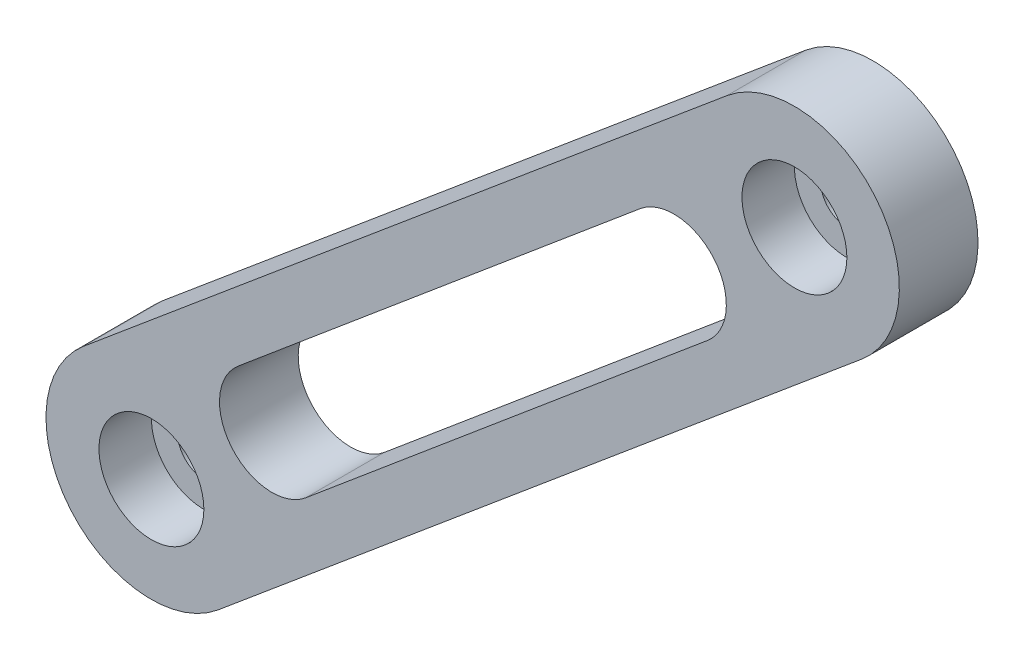
SolidWorks part; units mm, degrees
ref_plane "Front Plane" through (0, 0, 0) normal (0, 0, 1) x (1, 0, 0)
ref_plane "Top Plane" through (0, 0, 0) normal (0, 1, 0) x (1, 0, 0)
ref_plane "Right Plane" through (0, 0, 0) normal (1, 0, 0) x (0, 0, -1)
sketch "Sketch1" plane through (0, 0, 0) normal (0, 0, 1) x (1, 0, 0)
  line L0 (0, 0) -> (179.8502, 0) construction
  line L1 (8.1835, 0) -> (598.7674, 495.5587) construction
  line L2 (598.7674, 495.5587) -> (686.1477, 0) construction
  line L5 (563.0022, 498.7055) -> (407.2138, 368.2447)
  line L7 (595.6175, 459.7583) -> (439.8291, 329.2975)
  line L9 (550.1235, 454.7417) -> (452.8359, 373.1077) construction
  line L10 (558.2869, 445.0129) -> (460.9993, 363.3789)
  line L11 (541.9601, 464.4705) -> (444.6725, 382.8364)
  line L12 (423.6499, 348.6177) -> (407.2138, 368.2447) construction
  line L13 (423.6499, 348.6177) -> (439.8291, 329.2975) construction
  line L14 (563.0022, 498.7055) -> (595.6175, 459.7583) construction
  arc A0 (558.2869, 445.0129) -> (541.9601, 464.4705) centre (550.1235, 454.7417) ccw
  arc A1 (444.6725, 382.8364) -> (460.9993, 363.3789) centre (452.8359, 373.1077) ccw
  circle A2 centre (423.6499, 348.6177) radius 6.35
  arc A3 (407.2138, 368.2447) -> (439.8291, 329.2975) centre (423.5214, 348.7711) ccw
  circle A4 centre (579.3098, 479.2319) radius 6.35
  arc A5 (563.0022, 498.7055) -> (595.6175, 459.7583) centre (579.3098, 479.2319) cw
  point P4 (0, 0)
  point P6 (550.1235, 454.7417)
  point P12 (501.4797, 413.9247)
  point P24 (579.3098, 479.2319)
  dimension "D6" = 12.7
  dimension "D7" = 12.7
  dimension "D4" = 25.4
  dimension "D3" = 25.4
  dimension "D1" = 40
  dimension "D2" = 80
  dimension "D5" = 127
  dimension "D8" = 38.1
  dimension "D9" = 38.1
extrude "Boss-Extrude1" add sketch "Sketch1" along normal blind 19.05
sketch "Sketch2" plane through (0, 0, 19.05) normal (0, 0, 1) x (1, 0, 0)
  circle A0 centre (423.6499, 348.6177) radius 12.7
  circle A1 centre (579.3098, 479.2319) radius 12.7
  dimension "D1" = 25.4
extrude "Cut-Extrude1" cut sketch "Sketch2" against normal blind 12.7
